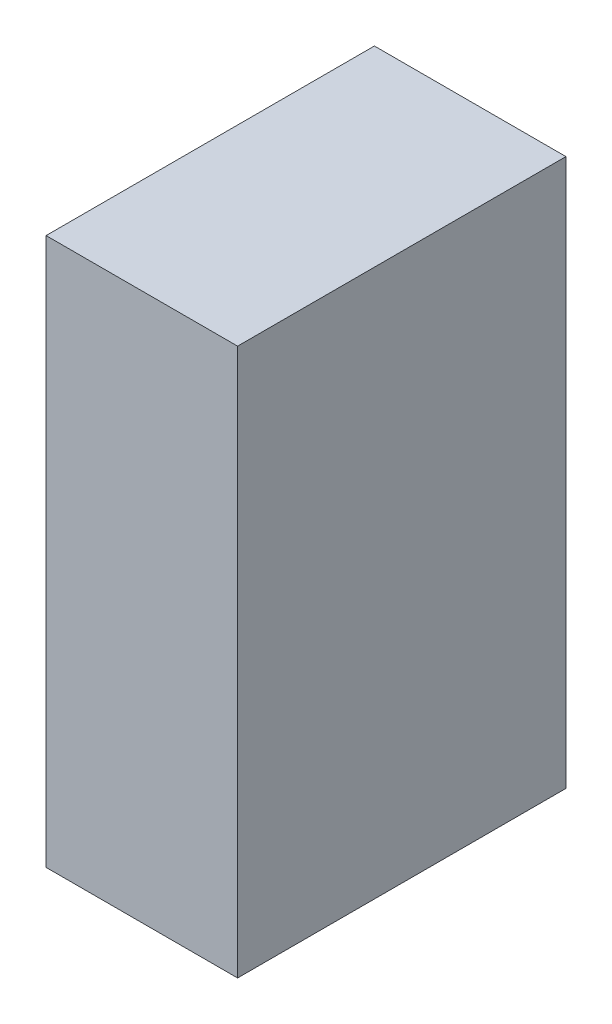
SolidWorks part; units mm, degrees
ref_plane "Front Plane" through (0, 0, 0) normal (0, 0, 1) x (1, 0, 0)
ref_plane "Top Plane" through (0, 0, 0) normal (0, 1, 0) x (1, 0, 0)
ref_plane "Right Plane" through (0, 0, 0) normal (1, 0, 0) x (0, 0, -1)
other "Configuration Table"
sketch "Sketch1" plane through (0, 0, 0) normal (0, 0, 1) x (1, 0, 0)
  line L1 (610, 180) -> (645, 180)
  line L2 (610, 180) -> (610, 280)
  line L3 (610, 280) -> (645, 280)
  line L4 (645, 180) -> (645, 280)
extrude "PACK_pano_servo_surucu_3_1" add sketch "Sketch1" against normal blind 60 from offset 188 separate body
